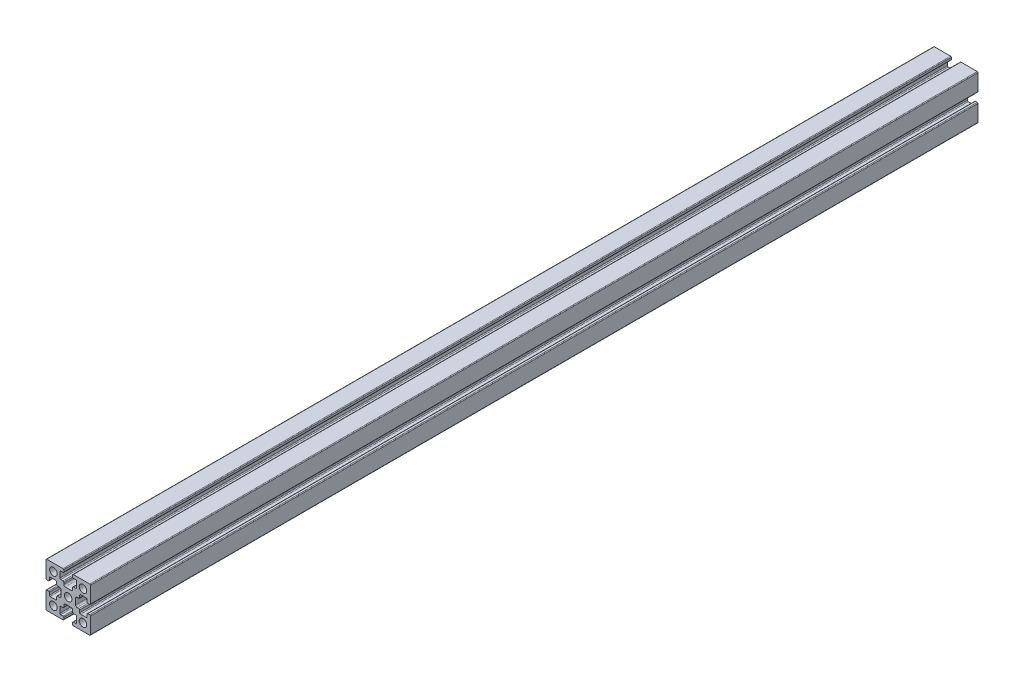
SolidWorks part; units mm, degrees
ref_plane "Front Plane" through (0, 0, 0) normal (0, 0, 1) x (1, 0, 0)
ref_plane "Top Plane" through (0, 0, 0) normal (0, 1, 0) x (1, 0, 0)
ref_plane "Right Plane" through (0, 0, 0) normal (1, 0, 0) x (0, 0, -1)
sketch "Sketch1" plane through (0, 0, 0) normal (0, 0, 1) x (1, 0, 0)
  line L0 (0, 0) -> (10.5807, 0) construction
  line L1 (0, 0) -> (0, -10.5807) construction
  line L2 (1.5, -7.5) -> (7.25, -7.5)
  line L3 (7.5, -7.25) -> (7.5, -1.5)
  line L4 (0, 0) -> (10.19, -10.19) construction
  line L5 (7.5, -1.5) -> (6.4, -1.5)
  line L6 (6.4, -1.5) -> (6.4, -2.85)
  line L7 (6.4, -2.85) -> (3.9, -2.85)
  line L9 (2.5, -1.5) -> (2.5, 0)
  line L12 (1.5, -2.5) -> (0, -2.5)
  line L14 (2.85, -6.4) -> (2.85, -3.9)
  line L15 (1.5, -6.4) -> (2.85, -6.4)
  line L16 (1.5, -7.5) -> (1.5, -6.4)
  line L17 (2.5, 0) -> (1.275, 0)
  line L18 (0, -1.275) -> (0, -2.5)
  line L19 (2.5, -1.5) -> (3.9, -1.5)
  line L20 (3.9, -1.5) -> (3.9, -2.85)
  line L21 (1.5, -3.9) -> (2.85, -3.9)
  line L22 (1.5, -2.5) -> (1.5, -3.9)
  arc A0 (1.275, 0) -> (0, -1.275) centre (0, 0) cw
  arc A1 (7.25, -7.5) -> (7.5, -7.25) centre (7.25, -7.25) ccw
  circle A2 centre (5, -5) radius 1.275
  dimension "D1" = 1.275
  dimension "D3" = 0.25
  dimension "D9" = 10
  dimension "D2" = 15
  dimension "D4" = 3
  dimension "D5" = 5.7
  dimension "D6" = 1.1
  dimension "D7" = 2.5
  dimension "D8" = 1.4
extrude "Boss-Extrude1" add sketch "Sketch1" along normal mid plane 300
fillet "Fillet2" radius 0.5 2 edges at (1.5, -2.5, 0) (2.5, -1.5, 0)
fillet "Fillet3" radius 0.3 6 edges at (2.85, -6.4, 0) (2.85, -3.9, 0) (1.5, -3.9, 0) (6.4, -2.85, 0) (3.9, -2.85, 0) (3.9, -1.5, 0)
fillet "Fillet1" radius 0.25 4 edges at (1.5, -7.5, 0) (1.5, -6.4, 0) (6.4, -1.5, 0) (7.5, -1.5, 0)
pattern_circular "CirPattern1" count 4 over 360 about axis through (0, 0, 0) along (0, 0, 1) of bodies 101
combine bodies "Combine1" bodies to combine 101 104 103 102
